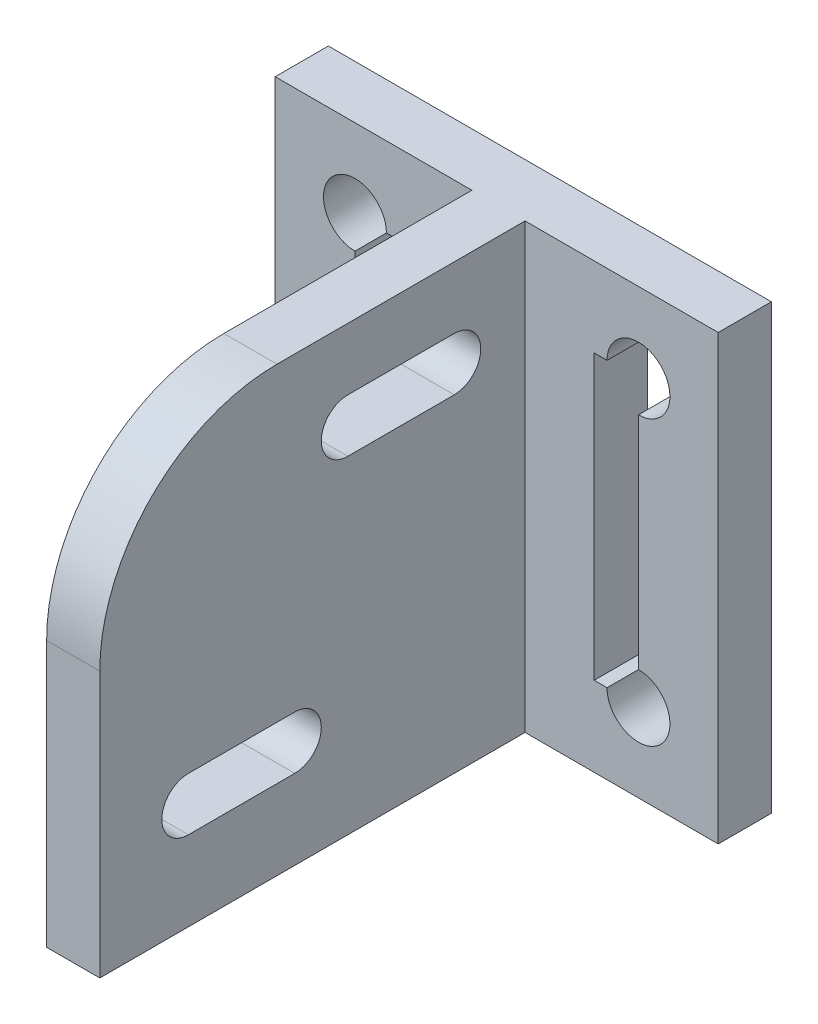
SolidWorks part; units mm, degrees
ref_plane "Plan de face" through (0, 0, 0) normal (0, 0, 1) x (1, 0, 0)
ref_plane "Plan de dessus" through (0, 0, 0) normal (0, 1, 0) x (1, 0, 0)
ref_plane "Plan de droite" through (0, 0, 0) normal (1, 0, 0) x (0, 0, -1)
sketch "Esquisse1" plane through (0, 0, 0) normal (0, 0, 1) x (1, 0, 0)
  line L1 (0, 0) -> (25, 0)
  line L2 (0, 0) -> (0, 25)
  line L3 (0, 25) -> (25, 25)
  line L4 (25, 0) -> (25, 25)
  dimension "D1" = 25
  dimension "D2" = 25
extrude "Boss.-Extru.1" add sketch "Esquisse1" along normal blind 3
sketch "Esquisse4" plane through (0, 0, 0) normal (0, 0, -1) x (-1, 0, 0)
  line L0 (-18.5, 9.155) -> (-18.5, 7.655) construction
  line L1 (-20.5, 4.5) -> (-18, 4.5)
  line L2 (-20.5, 4.5) -> (-20.5, 20.5)
  line L3 (-20.5, 20.5) -> (-18, 20.5)
  line L4 (-18, 4.5) -> (-18, 20.5)
  line L5 (-4.5, 20.5) -> (-7, 20.5)
  line L6 (-4.5, 20.5) -> (-4.5, 4.5)
  line L7 (-4.5, 4.5) -> (-7, 4.5)
  line L8 (-7, 20.5) -> (-7, 4.5)
  line L9 (-6.5, 9.395) -> (-6.5, 10.895) construction
  circle A0 centre (-20.5, 4.5) radius 1.775
  circle A1 centre (-20.5, 20.5) radius 1.775
  circle A2 centre (-4.5, 20.5) radius 1.775
  circle A3 centre (-4.5, 4.5) radius 1.775
  dimension "D1" = 0.5
  dimension "D2" = 0.5
extrude "Enlèv. mat.-Extru.1" cut sketch "Esquisse4" against normal blind 10 contours L2 A0 L1 | L1 A0 L2 | A1 L2 A0 L1 L4 L3 | L2 A1 L3 | L3 A1 L2 | L6 A2 L5 | L5 A2 L6 | A3 L6 A2 L5 L8 L7 | L6 A3 L7 | L7 A3 L6
sketch "Esquisse5" plane through (0, 0, 3) normal (0, 0, 1) x (1, 0, 0)
  line L0 (0, 0) -> (25, 0) construction
  line L1 (11.1, 0) -> (14.1, 0)
  line L2 (11.1, 0) -> (11.1, 25)
  line L3 (11.1, 25) -> (14.1, 25)
  line L4 (14.1, 0) -> (14.1, 25)
  line L5 (11.1, -48.2874) -> (11.1, 30.2229) construction
  line L6 (25, 25) -> (0, 25) construction
  dimension "D1" = 3
extrude "Boss.-Extru.3" add sketch "Esquisse5" along normal blind 24
sketch "Esquisse6" plane through (14.1, 0, 0) normal (1, 0, 0) x (0, 0, -1)
  line L0 (-2, 25) -> (-2, 0) construction
  line L1 (-27, 25) -> (-3, 25) construction
  line L2 (-27, 0) -> (-3, 0) construction
  line L3 (-2, -23) -> (-2, 30.2229) construction
  line L4 (-22, 6) -> (-16, 6) construction
  line L5 (-22, 7.5) -> (-16, 7.5)
  line L6 (-7, 20) -> (-13, 20) construction
  line L7 (-7, 18.5) -> (-13, 18.5)
  line L8 (-7, 21.5) -> (-13, 21.5)
  line L9 (-22, 4.5) -> (-16, 4.5)
  line L10 (-27, 0) -> (-27, 25) construction
  arc A2 (-7, 18.5) -> (-7, 21.5) centre (-7, 20) ccw
  arc A3 (-13, 21.5) -> (-13, 18.5) centre (-13, 20) ccw
  arc A4 (-22, 7.5) -> (-22, 4.5) centre (-22, 6) ccw
  arc A5 (-16, 4.5) -> (-16, 7.5) centre (-16, 6) ccw
  point P8 (-19, 6)
  point P16 (-10, 20)
  dimension "D1" = 6
  dimension "D2" = 1.5
  dimension "D5" = 1.5
  dimension "D6" = 4.5
  dimension "D7" = 5
  dimension "D3" = 3.5
  dimension "D4" = 6
  dimension "D8" = 5
extrude "Enlèv. mat.-Extru.2" cut sketch "Esquisse6" against normal blind 10
fillet "Congé1" radius 10 1 edges at (12.6, 25, 27)
